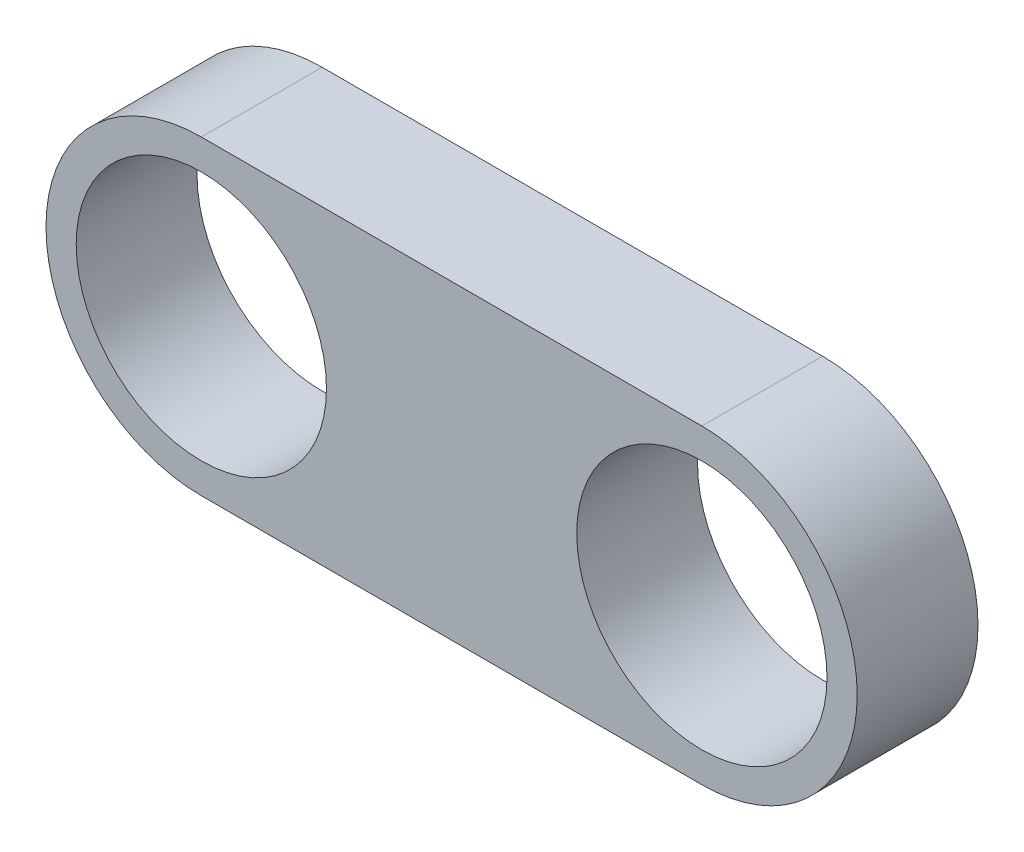
SolidWorks part; units mm, degrees
other "Детальный элемент3"
other "Детальный элемент4"
material "3.3320 (EN-AW 5019)"
ref_plane "Спереди" through (0, 0, 0) normal (0, 0, 1) x (1, 0, 0)
ref_plane "Сверху" through (0, 0, 0) normal (0, 1, 0) x (1, 0, 0)
ref_plane "Справа" through (0, 0, 0) normal (1, 0, 0) x (0, 0, -1)
sketch "Эскиз1" plane through (0, 0, 0) normal (0, 0, 1) x (1, 0, 0)
  line L0 (0, -14.1068) -> (0, 9) construction
  line L1 (14.5, 9) -> (-14.5, 9)
  line L2 (-24.6591, 0) -> (24.8812, 0) construction
  line L3 (14.5, -9) -> (-14.5, -9)
  arc A0 (14.5, 9) -> (14.5, -9) centre (14.5, 0) cw
  arc A1 (-14.5, 9) -> (-14.5, -9) centre (-14.5, 0) ccw
  point P10 (0, -9)
  dimension "D1" = 9
  dimension "D2" = 14.5
extrude "Бобышка-Вытянуть1" add sketch "Эскиз1" along normal blind 7
hole_wizard "Отверстие обработанное метчиком M16x1.51" positions "Эскиз5" profile "Эскиз3" tap size "M16x1.5" standard "Ansi Metric" end condition through all
sketch "Эскиз5" plane through (0, 0, 0) normal (0, 0, -1) x (-1, 0, 0)
  arc A0 (14.5, -9) -> (14.5, 9) centre (14.5, 0) ccw construction
  arc A1 (14.5, -9) -> (14.5, 9) centre (14.5, 0) ccw construction
  point P0 (14.5, 0)
sketch "Эскиз3" plane through (-14.5, 0, 0) normal (1, 0, 0) x (0, 1, 0)
  line L0 (0, 0) -> (0, 7)
  line L1 (0, 7) -> (7.25, 7)
  line L2 (7.25, 7) -> (7.25, 0)
  line L5 (7.25, 0) -> (0, 0)
  line L11 (0, -6.35) -> (0, 107.95) construction
  dimension "Диаметр проходного сверла" = 14.5
  dimension "Глубина проходного сверла" = 7
cosmetic thread "Отверстие резьбы1" parameters "D2"=16
mirror "Зеркальное отражение1" about plane through (0, 0, 0) normal (1, 0, 0) of "Отверстие обработанное метчиком M16x1.51"
